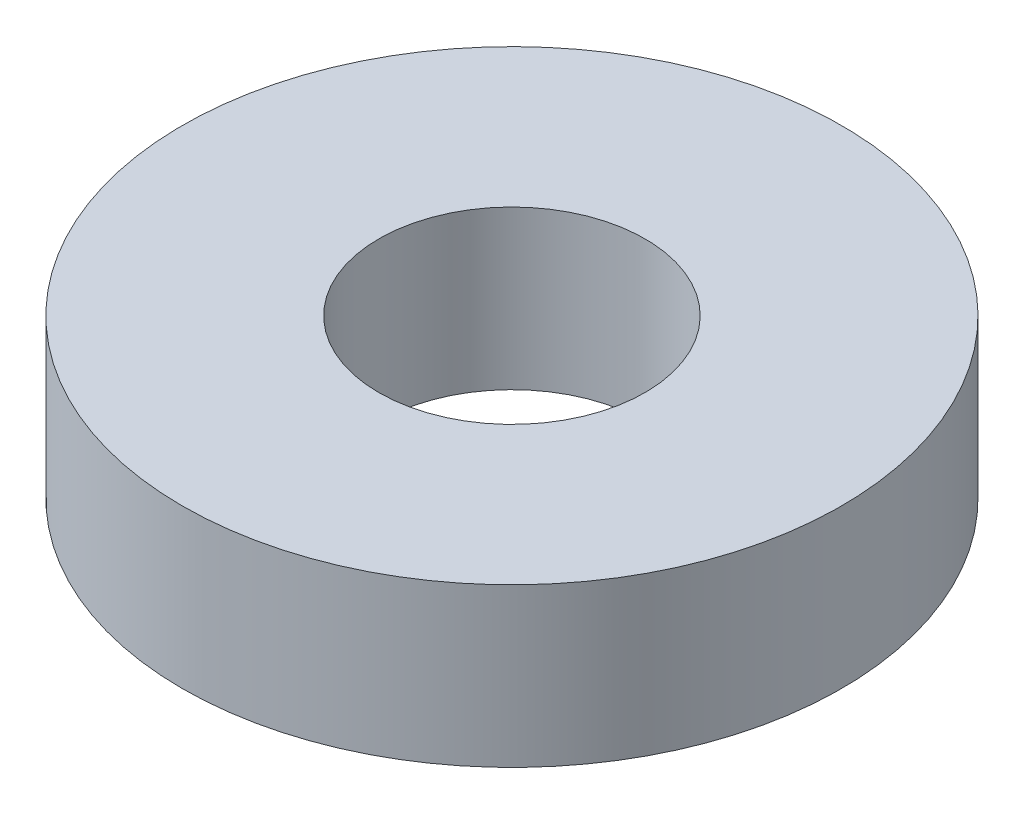
SolidWorks part; units mm, degrees
ref_plane "Płaszczyzna przednia" through (0, 0, 0) normal (0, 0, 1) x (1, 0, 0)
ref_plane "Płaszczyzna górna" through (0, 0, 0) normal (0, 1, 0) x (1, 0, 0)
ref_plane "Płaszczyzna prawa" through (0, 0, 0) normal (1, 0, 0) x (0, 0, -1)
sketch "Szkic1" plane through (0, -358.274, 0) normal (0, 1, 0) x (1, 0, 0)
  line L0 (-393.068, -130.1552) -> (-375.068, -130.1552)
  line L1 (-397.068, -126.1552) -> (-397.068, -94.1552)
  line L2 (-371.068, -126.1552) -> (-371.068, -94.1552)
  line L3 (-393.068, -90.1552) -> (-375.068, -90.1552)
  arc A0 (-397.068, -126.1552) -> (-393.068, -130.1552) centre (-393.068, -126.1552) ccw
  arc A1 (-375.068, -130.1552) -> (-371.068, -126.1552) centre (-375.068, -126.1552) ccw
  arc A2 (-371.068, -94.1552) -> (-375.068, -90.1552) centre (-375.068, -94.1552) ccw
  arc A3 (-397.068, -94.1552) -> (-393.068, -90.1552) centre (-393.068, -94.1552) cw
  dimension "D3" = 4
  dimension "D1" = 26
  dimension "D2" = 40
extrude "Dodanie-wyciągnięcie1" add sketch "Szkic1" along normal blind 6
sketch "Szkic2" plane through (0, -352.274, 0) normal (0, 1, 0) x (1, 0, 0)
  line L0 (-384.068, -130.1552) -> (-384.068, -90.1552) construction
  line L1 (-393.068, -130.1552) -> (-375.068, -130.1552) construction
  line L2 (-375.068, -90.1552) -> (-393.068, -90.1552) construction
  line L3 (-371.068, -110.1552) -> (-397.068, -110.1552) construction
  line L4 (-371.068, -126.1552) -> (-371.068, -94.1552) construction
  line L5 (-397.068, -94.1552) -> (-397.068, -126.1552) construction
sketch "Szkic3" plane through (0, -352.274, 0) normal (0, 1, 0) x (1, 0, 0)
  circle A0 centre (-384.068, -110.1552) radius 5.05
  dimension "D1" = 10.1
extrude "Wytnij-wyciągnięcie1" cut sketch "Szkic3" against normal through all
sketch "Szkic4" plane through (0, -352.274, 0) normal (0, 1, 0) x (1, 0, 0)
  circle A0 centre (-384.068, -110.1552) radius 12.5
  circle A2 centre (-384.068, -110.1552) radius 5.05 construction
  dimension "D1" = 0
  dimension "D2" = 25
extrude "Wytnij-wyciągnięcie2" cut sketch "Szkic4" against normal blind 10 flip side to cut
equation "\"tolerancja_wpusy\"=0.2"
equation "\"dlugosc_wpustu_duzy\"=20"
equation "\"srednica_otworu_M3\"=3.1"
equation "\"szerokosc_nogi_T\"=3.1"
equation "\"dlugosc_T_30\"=11"
equation "\"grubosc_na_nakretke_kwadrat\"=2"
equation "\"szerokosc_na_nakretke_kwadrat\"=5.85"
equation "\"wyokosc_nadstawki_T\"=0.5"
equation "\"dlugosc_T_20_6\"=14"
